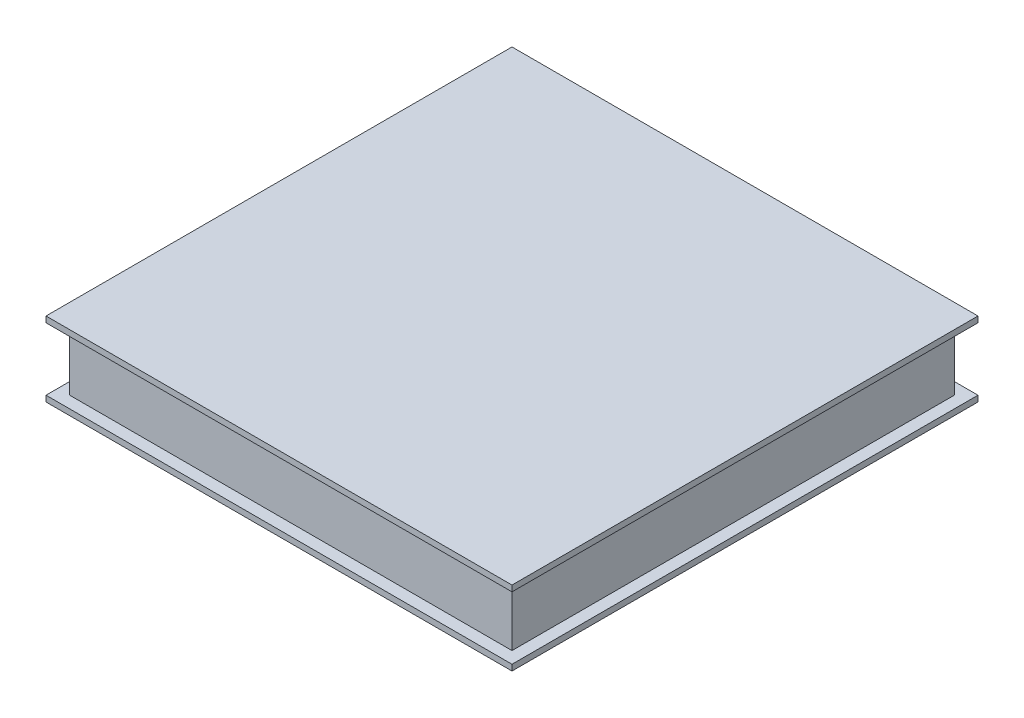
SolidWorks part; units mm, degrees
ref_plane "Front Plane" through (0, 0, 0) normal (0, 0, 1) x (1, 0, 0)
ref_plane "Top Plane" through (0, 0, 0) normal (0, 1, 0) x (1, 0, 0)
ref_plane "Right Plane" through (0, 0, 0) normal (1, 0, 0) x (0, 0, -1)
sketch "Sketch1" plane through (0, 0, 0) normal (0, 1, 0) x (1, 0, 0)
  line L1 (4.2182, -4.4638) -> (-5.7894, -4.4638)
  line L2 (4.2182, -4.4638) -> (4.2182, 5.5438)
  line L3 (4.2182, 5.5438) -> (-5.7894, 5.5438)
  line L4 (-5.7894, -4.4638) -> (-5.7894, 5.5438)
  line L5 (-5.5354, 5.2898) -> (3.9642, 5.2898)
  line L6 (-5.5354, 5.2898) -> (-5.5354, -4.2098)
  line L7 (-5.5354, -4.2098) -> (3.9642, -4.2098)
  line L8 (3.9642, 5.2898) -> (3.9642, -4.2098)
  dimension "D1" = 10.0076
  dimension "D2" = 10.0076
  dimension "D3" = 0.254
  dimension "D4" = 0.254
  dimension "D5" = 0.254
  dimension "D6" = 0.254
extrude "Boss-Extrude1" add sketch "Sketch1" along normal blind 0.127
sketch "Sketch2" plane through (0, 0, 0) normal (0, -1, 0) x (-1, 0, 0)
  line L1 (5.5354, 5.2898) -> (-3.9642, 5.2898)
  line L2 (5.5354, 5.2898) -> (5.5354, -4.2098)
  line L3 (5.5354, -4.2098) -> (-3.9642, -4.2098)
  line L4 (-3.9642, 5.2898) -> (-3.9642, -4.2098)
extrude "Boss-Extrude2" add sketch "Sketch2" against normal blind 1.6002
sketch "Sketch3" plane through (0, 1.6002, 0) normal (0, 1, 0) x (1, 0, 0)
  line L0 (-5.7894, -4.4638) -> (4.2182, -4.4638) construction
  line L1 (3.9642, -4.2098) -> (-5.5354, -4.2098)
  line L2 (3.9642, -4.2098) -> (3.9642, 5.2898)
  line L3 (3.9642, 5.2898) -> (-5.5354, 5.2898)
  line L4 (-5.5354, -4.2098) -> (-5.5354, 5.2898)
  line L5 (-5.7894, 5.5438) -> (4.2182, 5.5438)
  line L6 (-5.7894, 5.5438) -> (-5.7894, -4.4638)
  line L7 (-5.7894, -4.4638) -> (4.2182, -4.4638)
  line L8 (4.2182, 5.5438) -> (4.2182, -4.4638)
  line L9 (4.2182, -4.4638) -> (4.2182, 5.5438) construction
  line L11 (4.2182, 5.5438) -> (-5.7894, 5.5438) construction
  line L12 (-5.7894, 5.5438) -> (-5.7894, -4.4638) construction
  dimension "D1" = 0
  dimension "D2" = 0
  dimension "D3" = 0
  dimension "D4" = 0
extrude "Boss-Extrude3" add sketch "Sketch3" against normal blind 0.127
